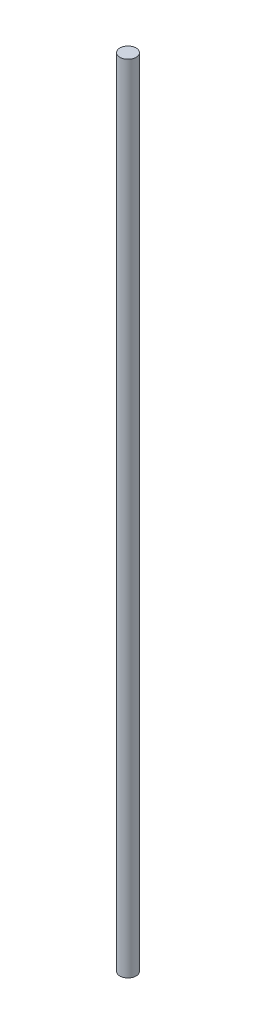
SolidWorks part; units mm, degrees
ref_plane "前基準面" through (0, 0, 0) normal (0, 0, 1) x (1, 0, 0)
ref_plane "上基準面" through (0, 0, 0) normal (0, 1, 0) x (1, 0, 0)
ref_plane "右基準面" through (0, 0, 0) normal (1, 0, 0) x (0, 0, -1)
sketch "草圖1" plane through (0, 0, 0) normal (0, 1, 0) x (1, 0, 0)
  circle A0 centre (0, 0) radius 0.5
  dimension "D1" = 1
extrude "填料-伸長1" add sketch "草圖1" along normal blind 49
